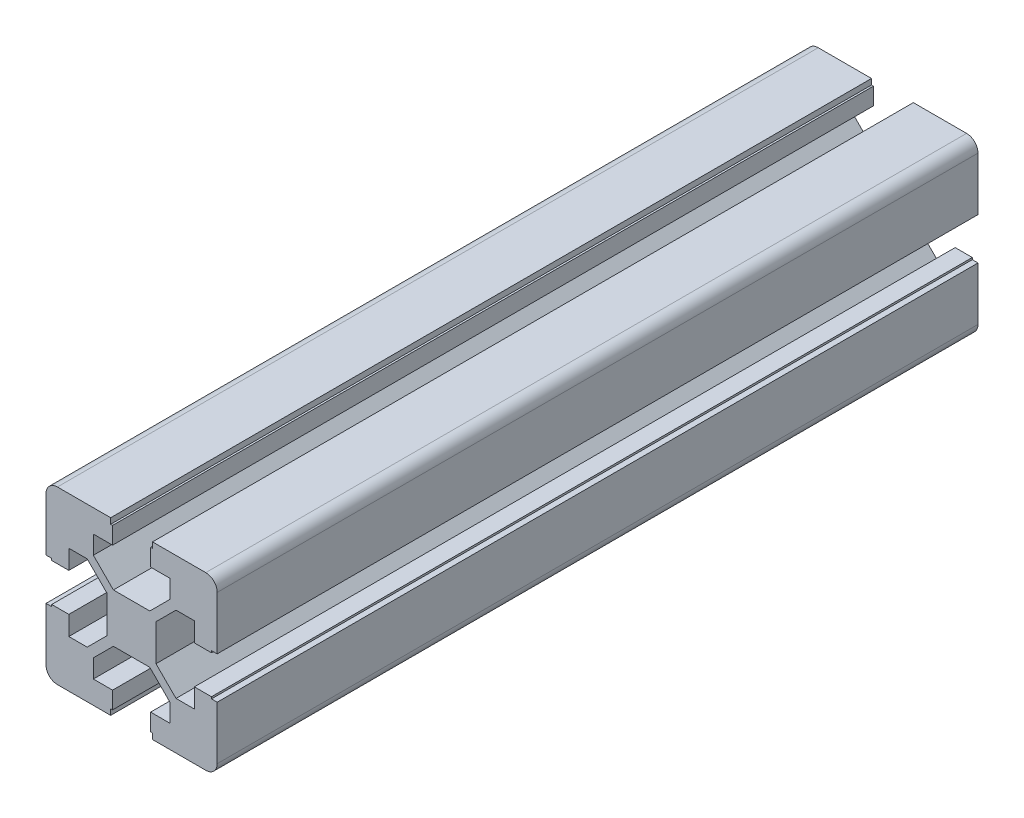
SolidWorks part; units mm, degrees
ref_plane "Front Plane" through (0, 0, 0) normal (0, 0, 1) x (1, 0, 0)
ref_plane "Top Plane" through (0, 0, 0) normal (0, 1, 0) x (1, 0, 0)
ref_plane "Right Plane" through (0, 0, 0) normal (1, 0, 0) x (0, 0, -1)
sketch "Sketch1" plane through (0, 0, 0) normal (0, 0, 1) x (1, 0, 0)
  line L0 (12.45, 34.175) -> (17.7151, 28.9099)
  line L2 (0, 3) -> (0, 42)
  line L3 (3, 45) -> (42, 45)
  line L5 (17.5, 39) -> (12.45, 39)
  line L6 (12.45, 39) -> (12.45, 34.175)
  line L7 (17.7151, 28.9099) -> (27.2849, 28.9099)
  line L8 (22.5, 28.9099) -> (22.5, 45) construction
  line L9 (27.5, 43.5) -> (27.5, 39)
  line L10 (28, 43.5) -> (27.5, 43.5)
  line L11 (28, 45) -> (28, 43.5)
  line L12 (32.55, 39) -> (32.55, 34.175)
  line L13 (27.5, 39) -> (32.55, 39)
  line L14 (32.55, 34.175) -> (27.2849, 28.9099)
  line L15 (45, 42) -> (45, 3)
  line L16 (42, 0) -> (3, 0)
  line L17 (34.175, 32.55) -> (28.9099, 27.2849)
  line L18 (39, 27.5) -> (39, 32.55)
  line L19 (39, 32.55) -> (34.175, 32.55)
  line L20 (28.9099, 27.2849) -> (28.9099, 17.7151)
  line L21 (43.5, 17.5) -> (39, 17.5)
  line L22 (43.5, 17) -> (43.5, 17.5)
  line L23 (45, 17) -> (43.5, 17)
  line L24 (39, 12.45) -> (34.175, 12.45)
  line L25 (39, 17.5) -> (39, 12.45)
  line L26 (34.175, 12.45) -> (28.9099, 17.7151)
  line L27 (45, 28) -> (43.5, 28)
  line L28 (43.5, 28) -> (43.5, 27.5)
  line L29 (43.5, 27.5) -> (39, 27.5)
  line L30 (28.9099, 22.5) -> (45, 22.5) construction
  line L31 (32.55, 10.825) -> (27.2849, 16.0901)
  line L32 (27.5, 6) -> (32.55, 6)
  line L33 (32.55, 6) -> (32.55, 10.825)
  line L34 (27.2849, 16.0901) -> (17.7151, 16.0901)
  line L35 (17.5, 1.5) -> (17.5, 6)
  line L36 (17, 45) -> (17, 43.5)
  line L37 (17, 43.5) -> (17.5, 43.5)
  line L38 (17.5, 43.5) -> (17.5, 39)
  line L39 (17, 1.5) -> (17.5, 1.5)
  line L40 (17, 0) -> (17, 1.5)
  line L41 (12.45, 6) -> (12.45, 10.825)
  line L42 (17.5, 6) -> (12.45, 6)
  line L43 (12.45, 10.825) -> (17.7151, 16.0901)
  line L44 (28, 0) -> (28, 1.5)
  line L45 (28, 1.5) -> (27.5, 1.5)
  line L46 (27.5, 1.5) -> (27.5, 6)
  line L47 (22.5, 16.0901) -> (22.5, 0) construction
  line L48 (10.825, 12.45) -> (16.0901, 17.7151)
  line L49 (6, 17.5) -> (6, 12.45)
  line L50 (6, 12.45) -> (10.825, 12.45)
  line L51 (16.0901, 17.7151) -> (16.0901, 27.2849)
  line L52 (1.5, 27.5) -> (6, 27.5)
  line L53 (1.5, 28) -> (1.5, 27.5)
  line L54 (0, 28) -> (1.5, 28)
  line L55 (6, 32.55) -> (10.825, 32.55)
  line L56 (6, 27.5) -> (6, 32.55)
  line L57 (10.825, 32.55) -> (16.0901, 27.2849)
  line L58 (0, 17) -> (1.5, 17)
  line L59 (1.5, 17) -> (1.5, 17.5)
  line L60 (1.5, 17.5) -> (6, 17.5)
  line L61 (16.0901, 22.5) -> (0, 22.5) construction
  arc A0 (3, 0) -> (0, 3) centre (3, 3) cw
  arc A1 (45, 3) -> (42, 0) centre (42, 3) cw
  arc A2 (42, 45) -> (45, 42) centre (42, 42) cw
  arc A3 (0, 42) -> (3, 45) centre (3, 42) cw
  point P15 (22.5, 22.5)
  point P18 (22.5, 22.5)
  point P23 (0, 0)
  point P78 (45, 45)
  point P81 (0, 45)
  dimension "D3" = 3
  dimension "D1" = 45
  dimension "D2" = 45
  dimension "D4" = 1.5
  dimension "D5" = 0.5
  dimension "D6" = 4.5
  dimension "D7" = 5.05
  dimension "D8" = 4.825
  dimension "D9" = 135
  dimension "D10" = 7.446
  dimension "D12" = 11
  dimension "D11" = 4
extrude "Boss-Extrude1" add sketch "Sketch1" along normal blind 200 contours A3 L2 L54 L53 L52 L56 L55 L57 L51 L48 L50 L49 L60 L59 L58 A0 L16 L40 L39 L35 L42 L41 L43 L34 L31 L33 L32 L46 L45 L44 A1 L15 L23 L22 L21 L25 L24 L26 L20 L17 L19 L18 L29 L28 L27 A2 L3 L11
